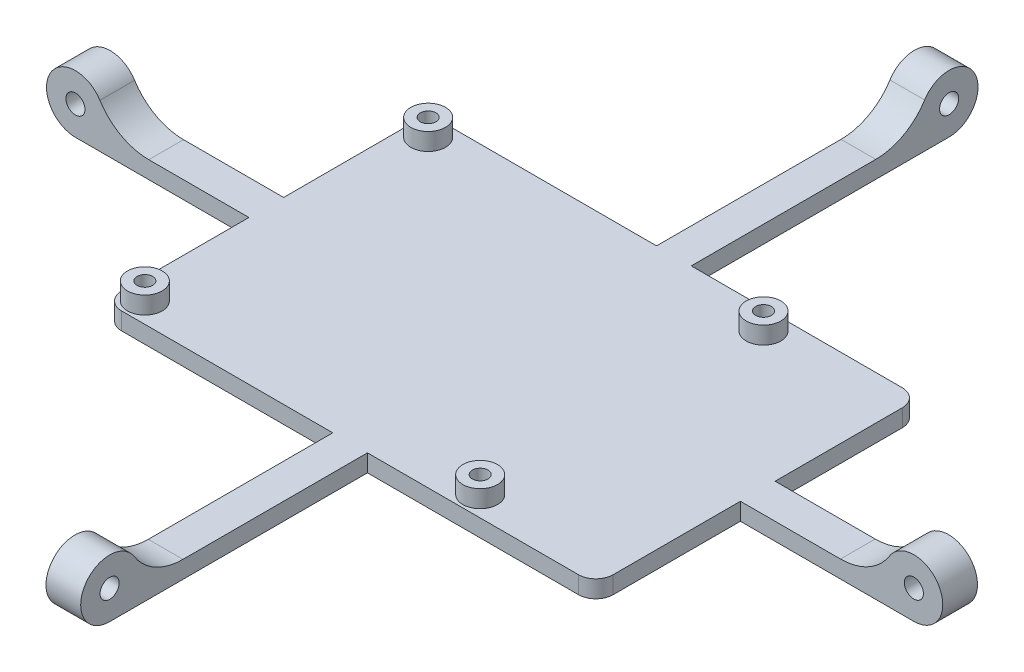
SolidWorks part; units mm, degrees
ref_plane "Front Plane" through (0, 0, 0) normal (0, 0, 1) x (1, 0, 0)
ref_plane "Top Plane" through (0, 0, 0) normal (0, 1, 0) x (1, 0, 0)
ref_plane "Right Plane" through (0, 0, 0) normal (1, 0, 0) x (0, 0, -1)
sketch "Sketch1" plane through (0, 0, 0) normal (0, 1, 0) x (1, 0, 0)
  line L0 (-39, 24.5) -> (-39, -24.5) construction
  line L1 (-39.5, -28) -> (39.5, -28)
  line L2 (-42.5, -25) -> (-42.5, 25)
  line L3 (-39.5, 28) -> (39.5, 28)
  line L4 (42.5, -25) -> (42.5, 25)
  line L5 (-42.5, -28) -> (42.5, 28) construction
  line L6 (-42.5, 28) -> (42.5, -28) construction
  line L7 (-39, 24.5) -> (19, 24.5) construction
  line L8 (-39, -24.5) -> (19, -24.5) construction
  circle A0 centre (-39, -24.5) radius 1.35
  circle A1 centre (-39, 24.5) radius 1.35
  circle A2 centre (19, 24.5) radius 1.35
  circle A3 centre (19, -24.5) radius 1.35
  arc A4 (39.5, 28) -> (42.5, 25) centre (39.5, 25) cw
  arc A5 (39.5, -28) -> (42.5, -25) centre (39.5, -25) ccw
  arc A6 (-39.5, -28) -> (-42.5, -25) centre (-39.5, -25) cw
  arc A7 (-42.5, 25) -> (-39.5, 28) centre (-39.5, 25) cw
  point P0 (0, 0)
  dimension "D3" = 2.7
  dimension "D8" = 3
  dimension "D1" = 56
  dimension "D2" = 85
  dimension "D4" = 3.5
  dimension "D5" = 3.5
  dimension "D6" = 3.5
  dimension "D7" = 58
extrude "Boss-Extrude1" add sketch "Sketch1" along normal blind 3
sketch "Sketch3" plane through (0, 3, 0) normal (0, 1, 0) x (1, 0, 0)
  line L0 (-72.5, 0) -> (72.5, 0) construction
  line L1 (42.5, -25) -> (42.5, 25) construction
  line L2 (0, 72.5) -> (0, -72.5) construction
  line L3 (-3, 3) -> (-72.5, 3)
  line L5 (-3, -3) -> (-72.5, -3)
  line L6 (-72.5, 3) -> (-72.5, -3)
  line L7 (-3, 3) -> (-3, 72.5)
  line L9 (42.5, 3) -> (42.5, -3)
  line L12 (3, 3) -> (3, 72.5)
  line L13 (3, 72.5) -> (-3, 72.5)
  line L14 (3, 3) -> (72.5, 3)
  line L15 (3, -3) -> (72.5, -3)
  line L16 (72.5, -3) -> (72.5, 3)
  line L17 (3, -3) -> (3, -72.5)
  line L18 (-3, -3) -> (-3, -72.5)
  line L19 (-3, -72.5) -> (3, -72.5)
  point P4 (0, 0)
  point P18 (0, 0)
  point P28 (0, 0)
  dimension "D1" = 30
  dimension "D2" = 6
  dimension "D3" = 4
extrude "Boss-Extrude3" add sketch "Sketch3" against normal blind 3 contours L5 L6 L3 L7 L13 L12 L14 L16 L15 L17 L19 L18
ref_axis "Axis1" through (0, 0, 0) along (0, 1, 0)
sketch "Sketch2" plane through (0, 3, 0) normal (0, 1, 0) x (1, 0, 0)
  circle A0 centre (19, 24.5) radius 1.35 construction
  circle A1 centre (19, -24.5) radius 1.35 construction
  circle A2 centre (-39, -24.5) radius 1.35 construction
  circle A3 centre (-39, 24.5) radius 1.35 construction
  circle A4 centre (19, 24.5) radius 1.35
  circle A5 centre (19, -24.5) radius 1.35
  circle A6 centre (-39, -24.5) radius 1.35
  circle A7 centre (-39, 24.5) radius 1.35
  circle A8 centre (-39, -24.5) radius 3
  circle A9 centre (-39, 24.5) radius 3
  circle A10 centre (19, 24.5) radius 3
  circle A11 centre (19, -24.5) radius 3
  dimension "D1" = 6
extrude "Boss-Extrude2" add sketch "Sketch2" along normal blind 3
sketch "Sketch4" plane through (0, 0, 3) normal (0, 0, 1) x (1, 0, 0)
  line L0 (-72.5, 0) -> (-42.5, 0) construction
  line L1 (-72.5, 0) -> (-72.5, 3) construction
  circle A0 centre (-72.5, 5) radius 1.65
  circle A1 centre (-72.5, 5) radius 5
  point P5 (0, 0)
  dimension "D1" = 3.3
  dimension "D2" = 10
extrude "Boss-Extrude4" add sketch "Sketch4" against normal up to surface (6 mm away) up to face at (-57.5, 1.5, -3)
fillet "Fillet1" radius 10 1 edges at (-67.9174, 3, 0)
sketch "Sketch6" plane through (3, 0, 0) normal (1, 0, 0) x (0, 0, -1)
  circle A0 centre (-72.5928, 4.9991) radius 5
  circle A1 centre (-72.5928, 4.9991) radius 1.65
  dimension "D1" = 3.3
  dimension "D2" = 10
extrude "Boss-Extrude5" add sketch "Sketch6" against normal up to surface (6 mm away) up to face at (-3, 1.5, 50.25)
fillet "Fillet2" radius 10 1 edges at (0, 3, 68.0099)
pattern_circular "CirPattern4" count 2 over 360 about axis through (0, 0, 0) along (0, 1, 0) of "Boss-Extrude3", "Boss-Extrude4", "Fillet1"
mirror "Mirror1" about plane through (0, 0, 0) normal (0, 0, 1) of "Fillet2", "Boss-Extrude5"
